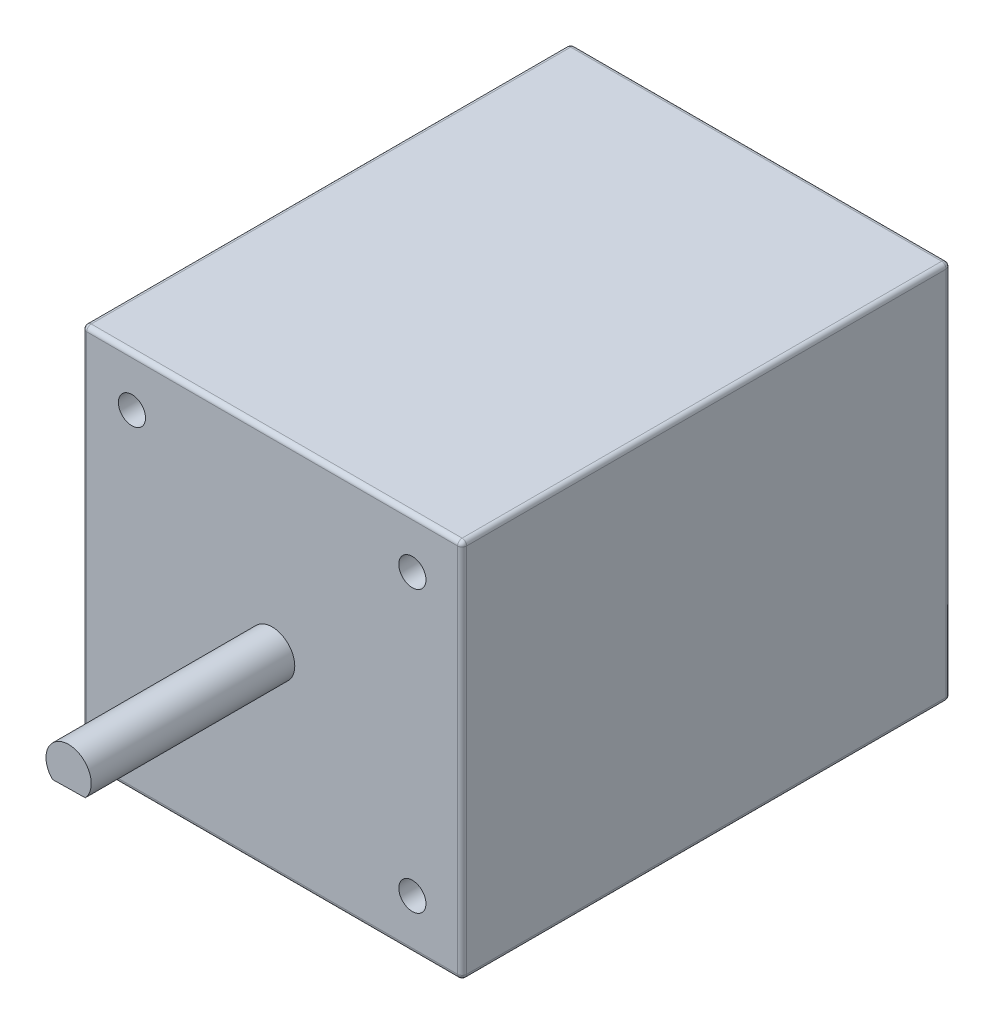
SolidWorks part; units mm, degrees
ref_plane "前视基准面" through (0, 0, 0) normal (0, 0, 1) x (1, 0, 0)
ref_plane "上视基准面" through (0, 0, 0) normal (0, 1, 0) x (1, 0, 0)
ref_plane "右视基准面" through (0, 0, 0) normal (1, 0, 0) x (0, 0, -1)
other "Configuration Table"
sketch "草图1" plane through (0, 0, 0) normal (0, 0, 1) x (1, 0, 0)
  line L1 (-21, -21) -> (21, -21)
  line L2 (-21, -21) -> (-21, 21)
  line L3 (-21, 21) -> (21, 21)
  line L4 (21, -21) -> (21, 21)
  line L5 (-21, -21) -> (21, 21) construction
  line L6 (-21, 21) -> (21, -21) construction
  point P0 (0, 0)
  dimension "D1" = 42
  dimension "D2" = 42
extrude "凸台-拉伸1" add sketch "草图1" along normal blind 54
sketch "草图2" plane through (0, 0, 0) normal (0, 0, 1) x (1, 0, 0)
  line L0 (-1.7858, -1.7495) -> (1.8444, -1.6876)
  arc A0 (1.8444, -1.6876) -> (-1.7858, -1.7495) centre (0, 0) ccw
  point P16 (0, 0)
  point P17 (0, 0)
  dimension "D1" = 5
extrude "凸台-拉伸2" add sketch "草图2" along normal blind 22.5 from surface at 54 starting at face at (0, 0, 54)
fillet "圆角1" radius 0.5 12 edges at (21, 0, 54) (21, 0, 0) (0, -21, 54) (21, -21, 27) (0, -21, 0) (-21, 0, 54) (-21, -21, 27) (-21, 0, 0) (21, 21, 27) (0, 21, 54) (-21, 21, 27) (0, 21, 0)
sketch "草图3" plane through (0, 0, 0) normal (0, 0, 1) x (1, 0, 0)
  circle A0 centre (-15.5, 15.5) radius 1.5
  circle A3 centre (15.5, 15.5) radius 1.5
  circle A4 centre (15.5, -15.5) radius 1.5
  circle A5 centre (-15.5, -15.5) radius 1.5
  point P16 (0, 0)
  dimension "D1" = 3
  dimension "D2" = 15.5
  dimension "D3" = 15.5
  dimension "D4" = 4
extrude "切除-拉伸1" cut sketch "草图3" against normal blind 10 from surface at 54 starting at face at (0, 0, 54)
